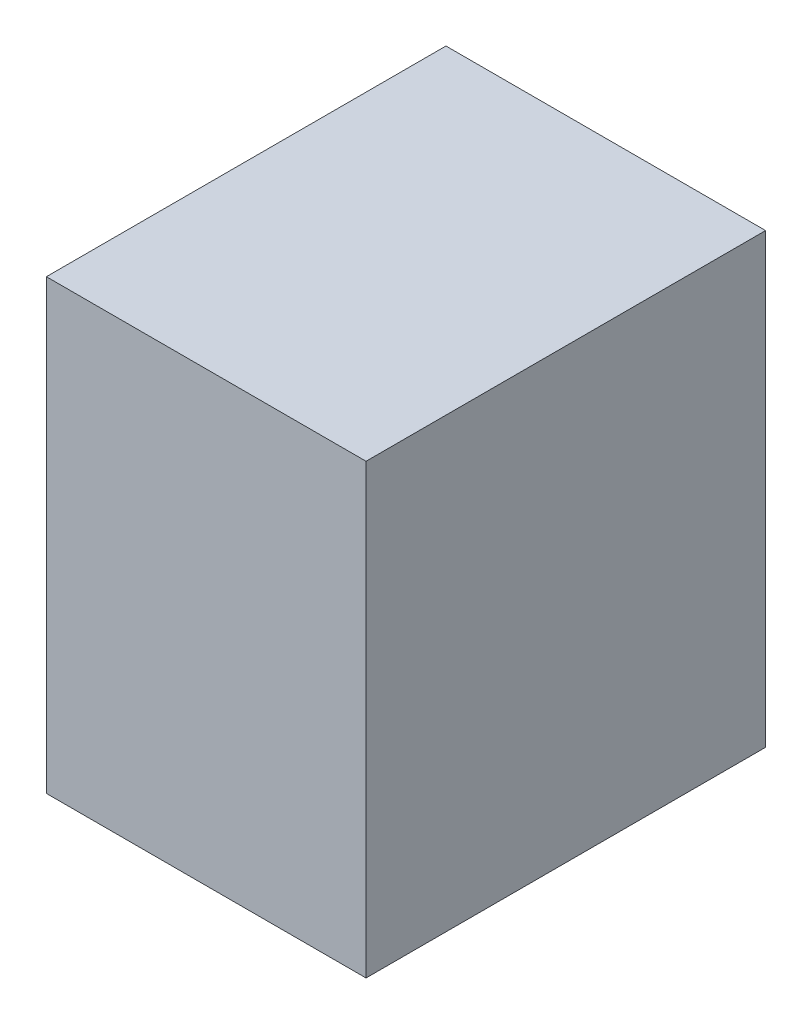
SolidWorks part; units mm, degrees
ref_plane "Спереди" through (0, 0, 0) normal (0, 0, 1) x (1, 0, 0)
ref_plane "Сверху" through (0, 0, 0) normal (0, 1, 0) x (1, 0, 0)
ref_plane "Справа" through (0, 0, 0) normal (1, 0, 0) x (0, 0, -1)
sketch "Эскиз1" plane through (0, 0, 0) normal (0, 1, 0) x (1, 0, 0)
  line L1 (0, 0) -> (200, 0)
  line L2 (0, 0) -> (0, 250)
  line L3 (0, 250) -> (200, 250)
  line L4 (200, 0) -> (200, 250)
  dimension "D1" = 250
  dimension "D2" = 200
extrude "Бобышка-Вытянуть1" add sketch "Эскиз1" along normal blind 280
